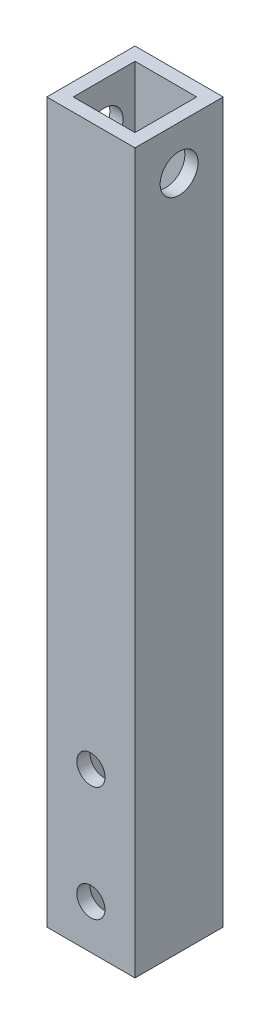
SolidWorks part; units mm, degrees
material "5052-H34"
ref_plane "正面" through (0, 0, 0) normal (0, 0, 1) x (1, 0, 0)
ref_plane "平面" through (0, 0, 0) normal (0, 1, 0) x (1, 0, 0)
ref_plane "右側面" through (0, 0, 0) normal (1, 0, 0) x (0, 0, -1)
sketch "ｽｹｯﾁ1" plane through (0, 0, 0) normal (0, 1, 0) x (1, 0, 0)
  line L1 (-5, 5) -> (5, 5)
  line L2 (-5, 5) -> (-5, -5)
  line L3 (-5, -5) -> (5, -5)
  line L4 (5, 5) -> (5, -5)
  line L5 (-5, 5) -> (5, -5) construction
  line L6 (-5, -5) -> (5, 5) construction
  point P0 (0, 0)
  dimension "D1" = 10
  dimension "D2" = 10
extrude "押し出し-薄板1" add sketch "ｽｹｯﾁ1" along normal blind 81.5 thin
sketch "ｽｹｯﾁ2" plane through (0, 0, 5) normal (0, 0, 1) x (1, 0, 0)
  line L0 (0, 0) -> (0, 18) construction
  circle A0 centre (0, 18) radius 1.6
  circle A1 centre (0, 5) radius 1.6
  dimension "D1" = 3.2
  dimension "D2" = 5
  dimension "D3" = 13
extrude "ｶｯﾄ - 押し出し1" cut sketch "ｽｹｯﾁ2" against normal through all
sketch "ｽｹｯﾁ3" plane through (5, 0, 0) normal (1, 0, 0) x (0, 0, -1)
  line L0 (0, 81.5) -> (0, 76.5) construction
  line L1 (-5, 81.5) -> (5, 81.5) construction
  circle A0 centre (0, 76.5) radius 2.15
  dimension "D2" = 4.3
  dimension "D1" = 5
extrude "ｶｯﾄ - 押し出し2" cut sketch "ｽｹｯﾁ3" against normal through all
